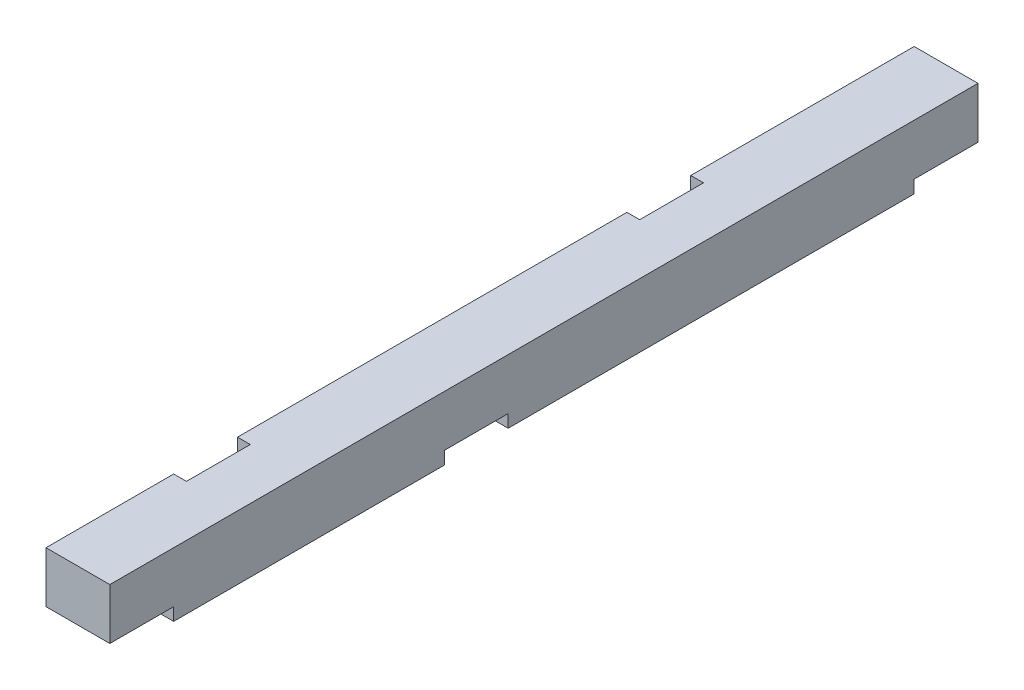
SolidWorks part; units mm, degrees
ref_plane "Plan de face" through (0, 0, 0) normal (0, 0, 1) x (1, 0, 0)
ref_plane "Plan de dessus" through (0, 0, 0) normal (0, 1, 0) x (1, 0, 0)
ref_plane "Plan de droite" through (0, 0, 0) normal (1, 0, 0) x (0, 0, -1)
sketch "Esquisse1" plane through (0, 0, 0) normal (0, 0, 1) x (1, 0, 0)
  line L1 (0, 0) -> (10, 0)
  line L2 (0, 0) -> (0, 10)
  line L3 (0, 10) -> (10, 10)
  line L4 (10, 0) -> (10, 10)
  dimension "D1" = 10
  dimension "D2" = 10
extrude "Boss.-Extru.1" add sketch "Esquisse1" along normal blind 136
sketch "Esquisse2" plane through (10, 0, 0) normal (1, 0, 0) x (0, 0, -1)
  line L0 (-136, 0) -> (-136, 10) construction
  line L1 (-136, 2) -> (-126, 2)
  line L2 (-136, 2) -> (-136, 0)
  line L3 (-136, 0) -> (-126, 0)
  line L4 (-126, 2) -> (-126, 0)
  line L5 (-136, 0) -> (0, 0) construction
  line L6 (-136, 0) -> (0, 0) construction
  line L7 (-83.6, 2) -> (-73.6, 2)
  line L8 (-83.6, 2) -> (-83.6, 0)
  line L9 (-83.6, 0) -> (-73.6, 0)
  line L10 (-73.6, 2) -> (-73.6, 0)
  line L12 (-10, 2) -> (0, 2)
  line L13 (-10, 2) -> (-10, 0)
  line L14 (-10, 0) -> (0, 0)
  line L15 (0, 2) -> (0, 0)
  dimension "D1" = 10
  dimension "D2" = 2
  dimension "D3" = 10
  dimension "D4" = 2
  dimension "D5" = 42.4
  dimension "D6" = 10
  dimension "D7" = 2
extrude "Enlèv. mat.-Extru.1" cut sketch "Esquisse2" against normal through all
sketch "Esquisse3" plane through (0, 0, 0) normal (-1, 0, 0) x (0, 0, 1)
  line L1 (35, 10) -> (45, 10)
  line L2 (35, 10) -> (35, 0)
  line L3 (35, 0) -> (45, 0)
  line L4 (45, 10) -> (45, 0)
  line L7 (0, 10) -> (0, 2) construction
  dimension "D1" = 10
  dimension "D2" = 35
extrude "Enlèv. mat.-Extru.2" cut sketch "Esquisse3" against normal blind 2
sketch "Esquisse4" plane through (0, 0, 0) normal (-1, 0, 0) x (0, 0, 1)
  line L0 (126, 0) -> (83.6, 0) construction
  line L1 (106, 10) -> (116, 10)
  line L2 (106, 10) -> (106, 0)
  line L3 (106, 0) -> (116, 0)
  line L4 (116, 10) -> (116, 0)
  line L5 (136, 10) -> (136, 2) construction
  line L6 (136, 10) -> (45, 10) construction
  dimension "D1" = 10
  dimension "D3" = 20
extrude "Enlèv. mat.-Extru.3" cut sketch "Esquisse4" against normal blind 2
